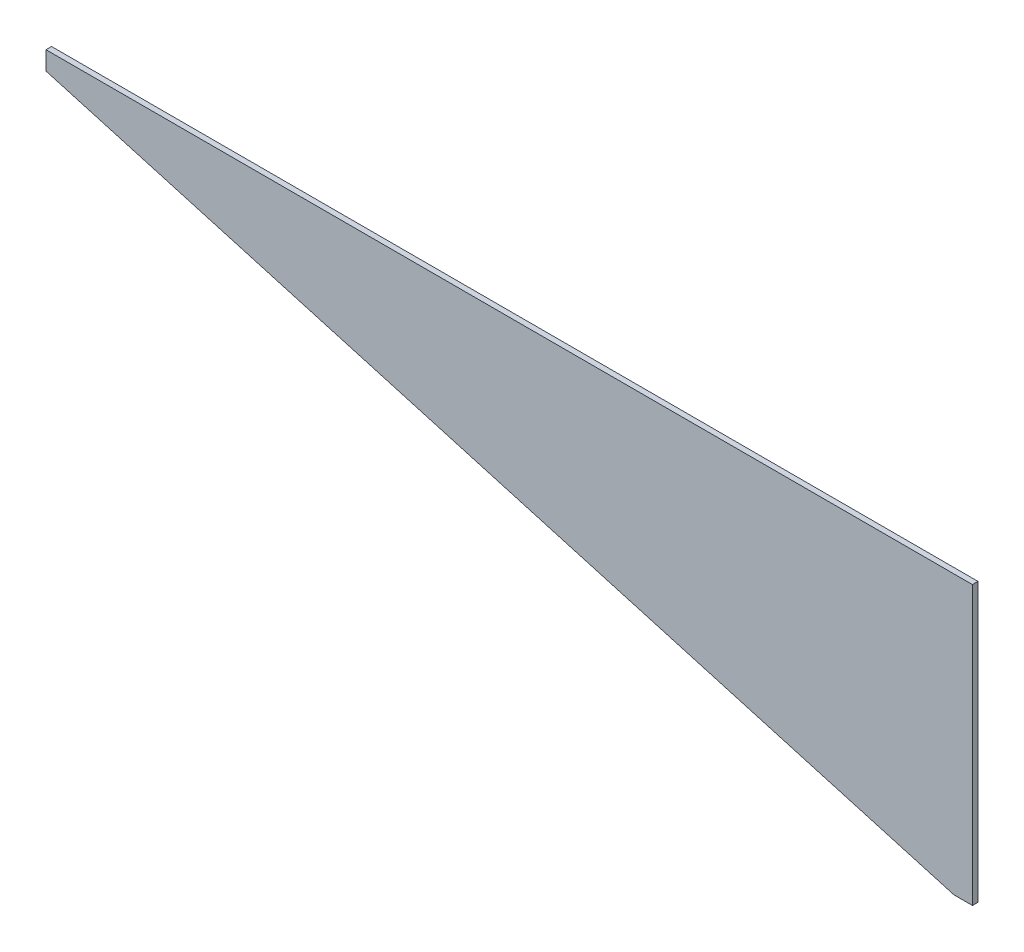
SolidWorks part; units mm, degrees
ref_plane "Front Plane" through (0, 0, 0) normal (0, 0, 1) x (1, 0, 0)
ref_plane "Top Plane" through (0, 0, 0) normal (0, 1, 0) x (1, 0, 0)
ref_plane "Right Plane" through (0, 0, 0) normal (1, 0, 0) x (0, 0, -1)
sketch "Sketch1" plane through (0, 0, 0) normal (0, 0, 1) x (1, 0, 0)
  line L0 (0, 0) -> (0, 150)
  line L1 (0, 150) -> (-500, 150)
  line L2 (-500, 150) -> (-500, 140)
  line L3 (-500, 140) -> (-10, 0)
  line L4 (-10, 0) -> (0, 0)
  dimension "D1" = 150
  dimension "D2" = 500
  dimension "D3" = 10
  dimension "D4" = 10
extrude "Boss-Extrude1" add sketch "Sketch1" along normal blind 3
